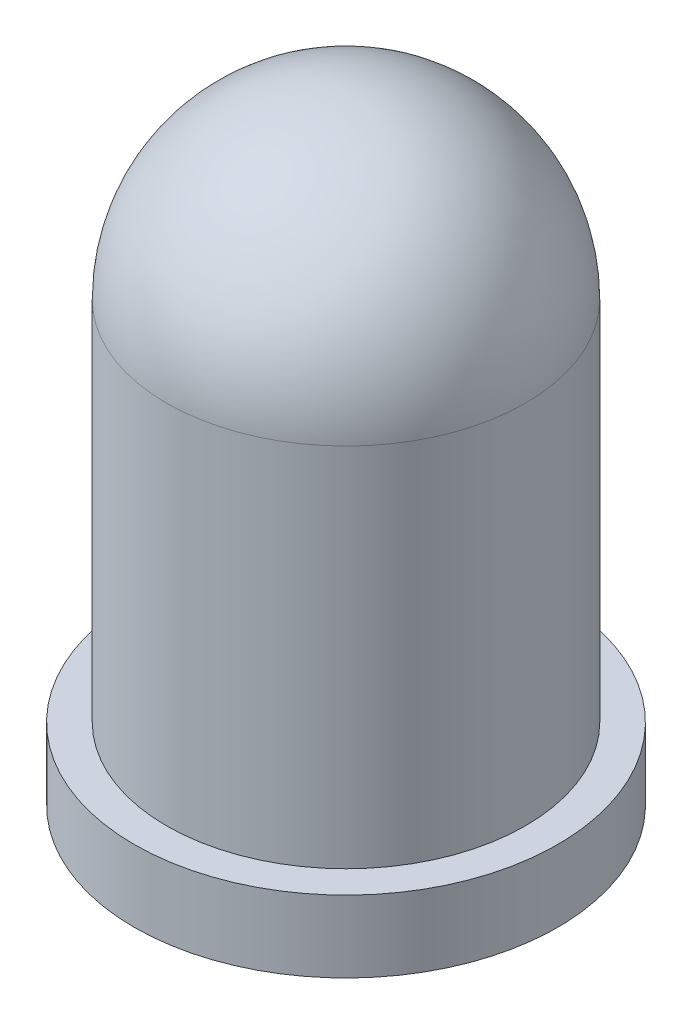
SolidWorks part; units mm, degrees
ref_plane "Front Plane" through (0, 0, 0) normal (0, 0, 1) x (1, 0, 0)
ref_plane "Top Plane" through (0, 0, 0) normal (0, 1, 0) x (1, 0, 0)
ref_plane "Right Plane" through (0, 0, 0) normal (1, 0, 0) x (0, 0, -1)
sketch "Sketch1" plane through (0, 0, 0) normal (1, 0, 0) x (0, 0, -1)
  line L0 (2.5, 1) -> (2.95, 1)
  line L2 (2.5, 1) -> (2.5, 6.1)
  line L9 (0, 0) -> (2.95, 0)
  line L10 (2.95, 1) -> (2.95, 0)
  line L11 (0, 8.6) -> (0, 0)
  arc A0 (0, 8.6) -> (2.5, 6.1) centre (0, 6.1) cw
  dimension "D2" = 1
  dimension "D1" = 8.6
  dimension "D3" = 2.5
  dimension "D4" = 0.45
revolve "Revolve2" add sketch "Sketch1" angle 360 about L11
